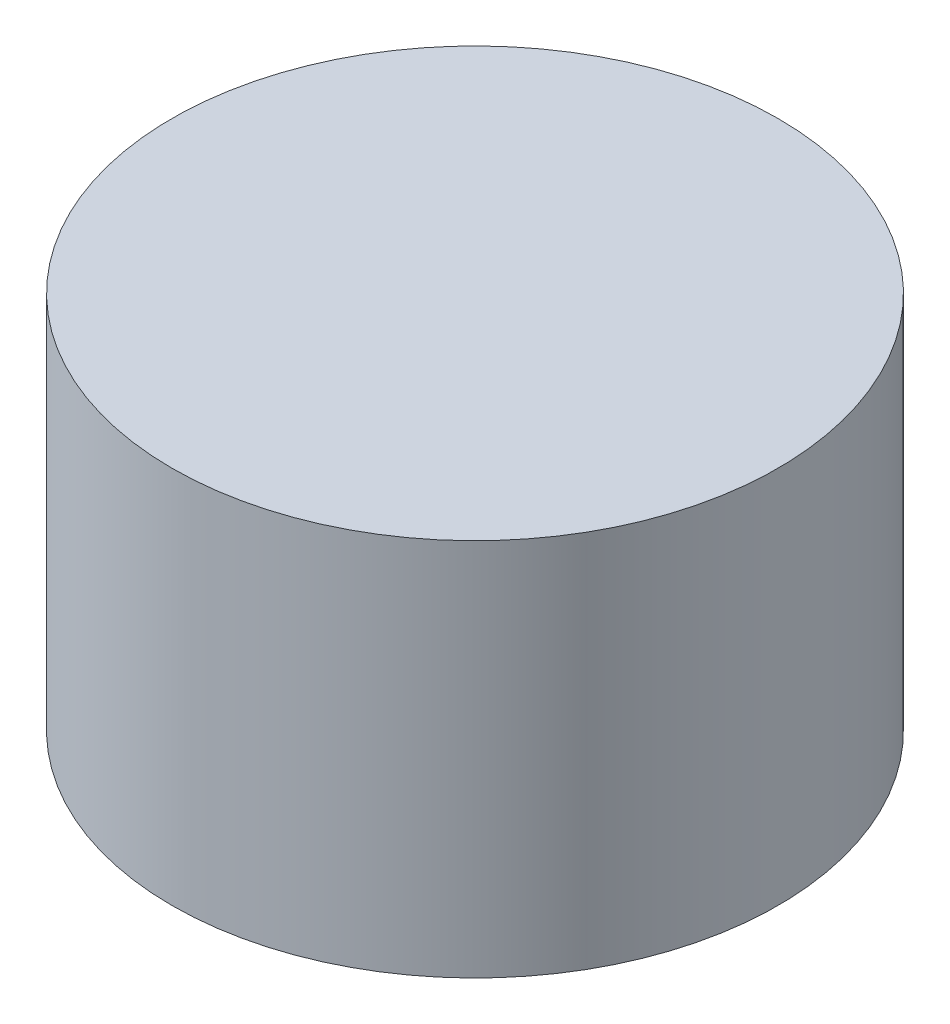
SolidWorks part; units mm, degrees
ref_plane "Front Plane" through (0, 0, 0) normal (0, 0, 1) x (1, 0, 0)
ref_plane "Top Plane" through (0, 0, 0) normal (0, 1, 0) x (1, 0, 0)
ref_plane "Right Plane" through (0, 0, 0) normal (1, 0, 0) x (0, 0, -1)
sketch "Sketch1" plane through (0, 0, 0) normal (0, 1, 0) x (1, 0, 0)
  circle A0 centre (0, 0) radius 4
  dimension "D1" = 8
extrude "Boss-Extrude1" add sketch "Sketch1" along normal blind 5
